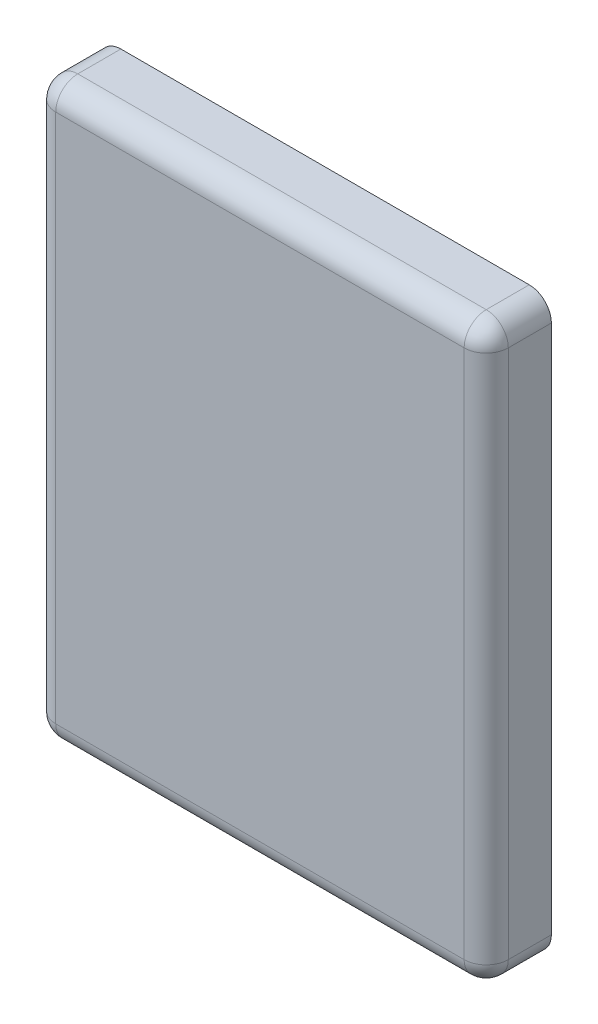
SolidWorks part; units mm, degrees
ref_plane "Alzado" through (0, 0, 0) normal (1, 0, 0) x (0, 1, 0)
ref_plane "Planta" through (0, 0, 0) normal (0, 0, 1) x (0, 1, 0)
ref_plane "Vista lateral" through (0, 0, 0) normal (0, 1, 0) x (-1, 0, 0)
sketch "Croquis1" plane through (0, 0, 0) normal (0, 0, 1) x (0, 1, 0)
  line L1 (-260, -205) -> (260, -205)
  line L2 (-260, -205) -> (-260, 205)
  line L3 (-260, 205) -> (260, 205)
  line L4 (260, -205) -> (260, 205)
  line L5 (-260, -205) -> (260, 205) construction
  line L6 (-260, 205) -> (260, -205) construction
  point P0 (0, 0)
  dimension "D1" = 520
  dimension "D2" = 410
extrude "Saliente-Extruir1" add sketch "Croquis1" along normal blind 9
sketch "Croquis2" plane through (0, 0, 9) normal (0, 0, 1) x (1, 0, 0)
  line L4 (205, 260) -> (-205, 260)
  line L5 (-205, 260) -> (-205, -260)
  line L6 (-205, -260) -> (205, -260)
  line L7 (205, -260) -> (205, 260)
  line L8 (205, 260) -> (-205, 260)
  line L9 (-205, 260) -> (-205, -260)
  line L10 (-205, -260) -> (205, -260)
  line L11 (205, -260) -> (205, 260)
  dimension "D1" = 0
extrude "Saliente-Extruir2" add sketch "Croquis2" along normal blind 50
fillet "Redondeo1" radius 20 8 edges at (-205, -260, 29.5) (-205, 260, 29.5) (-205, 0, 59) (0, -260, 59) (0, 260, 59) (205, 260, 29.5) (205, -260, 29.5) (205, 0, 59)
